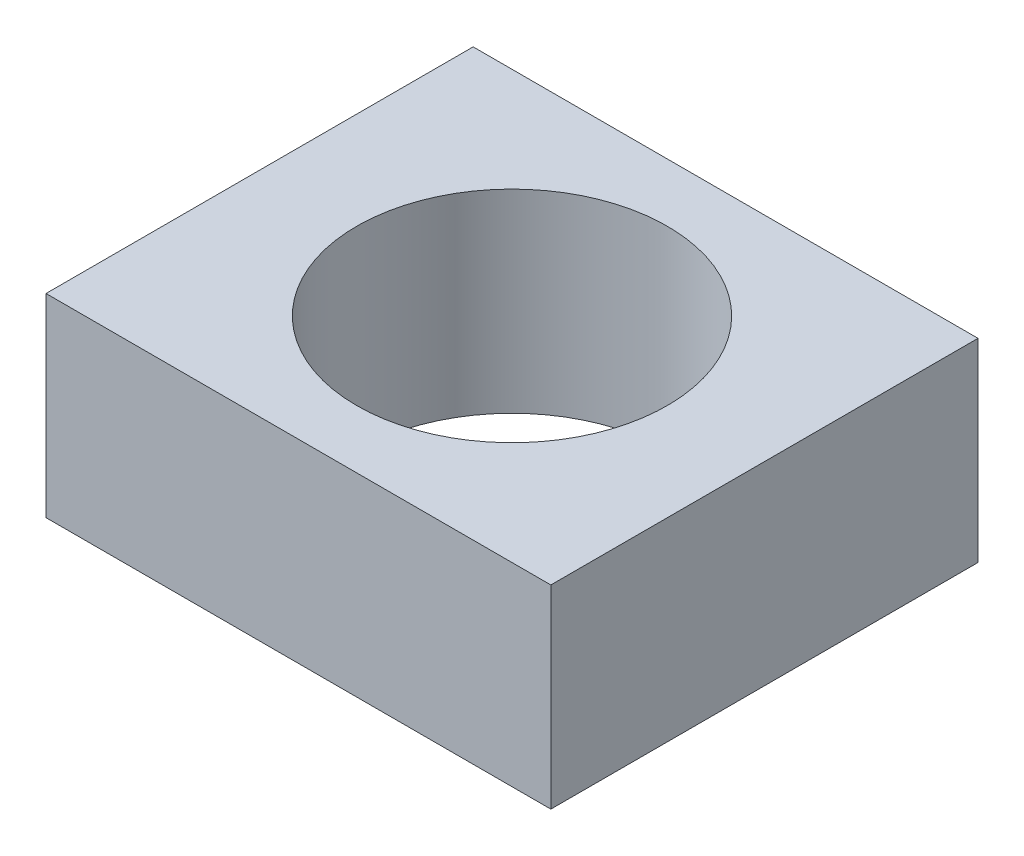
SolidWorks part; units mm, degrees
ref_plane "Front Plane" through (0, 0, 0) normal (0, 0, 1) x (1, 0, 0)
ref_plane "Top Plane" through (0, 0, 0) normal (0, 1, 0) x (1, 0, 0)
ref_plane "Right Plane" through (0, 0, 0) normal (1, 0, 0) x (0, 0, -1)
sketch "Sketch2" plane through (0, 0, 0) normal (0, 1, 0) x (1, 0, 0)
  line L1 (-6.5, 5.5) -> (6.5, 5.5)
  line L2 (-6.5, 5.5) -> (-6.5, -5.5)
  line L3 (-6.5, -5.5) -> (6.5, -5.5)
  line L4 (6.5, 5.5) -> (6.5, -5.5)
  line L5 (0, -5.5) -> (0, 5.5) construction
  line L6 (-6.5, 0) -> (6.5, 0) construction
  point P0 (0, 0)
  dimension "D1" = 13
  dimension "D2" = 11
extrude "Boss-Extrude2" add sketch "Sketch2" along normal blind 5
sketch "Sketch3" plane through (0, 5, 0) normal (0, 1, 0) x (1, 0, 0)
  circle A0 centre (0, 0) radius 4
  dimension "D1" = 8
extrude "Cut-Extrude1" cut sketch "Sketch3" against normal blind 5
